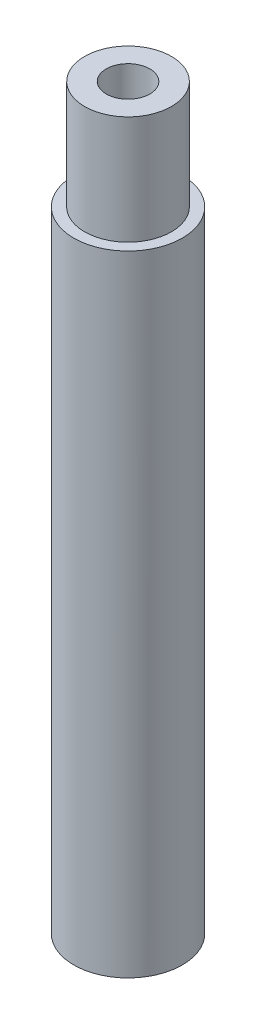
SolidWorks part; units mm, degrees
ref_plane "Front Plane" through (0, 0, 0) normal (0, 0, 1) x (1, 0, 0)
ref_plane "Top Plane" through (0, 0, 0) normal (0, 1, 0) x (1, 0, 0)
ref_plane "Right Plane" through (0, 0, 0) normal (1, 0, 0) x (0, 0, -1)
sketch "Sketch1" plane through (0, 0, 0) normal (0, 1, 0) x (1, 0, 0)
  circle A0 centre (0, 0) radius 6.3754
  circle A1 centre (0, 0) radius 15.875
  dimension "D1" = 12.7508
  dimension "D2" = 31.75
extrude "Boss-Extrude1" add sketch "Sketch1" along normal blind 203.2
sketch "Sketch2" plane through (0, 0, 0) normal (0, -1, 0) x (1, 0, 0)
  circle A0 centre (0, 0) radius 12.7
  circle A1 centre (0, 0) radius 15.875 construction
  circle A2 centre (0, 0) radius 15.875
  dimension "D1" = 25.4
extrude "Boss-Extrude2" add sketch "Sketch2" along normal blind 12.7
sketch "Sketch3" plane through (0, 203.2, 0) normal (0, 1, 0) x (1, 0, 0)
  circle A0 centre (0, 0) radius 12.7
  circle A1 centre (0, 0) radius 15.875 construction
  circle A2 centre (0, 0) radius 15.875
  dimension "D1" = 25.4
extrude "Cut-Extrude1" cut sketch "Sketch3" against normal blind 31.75
